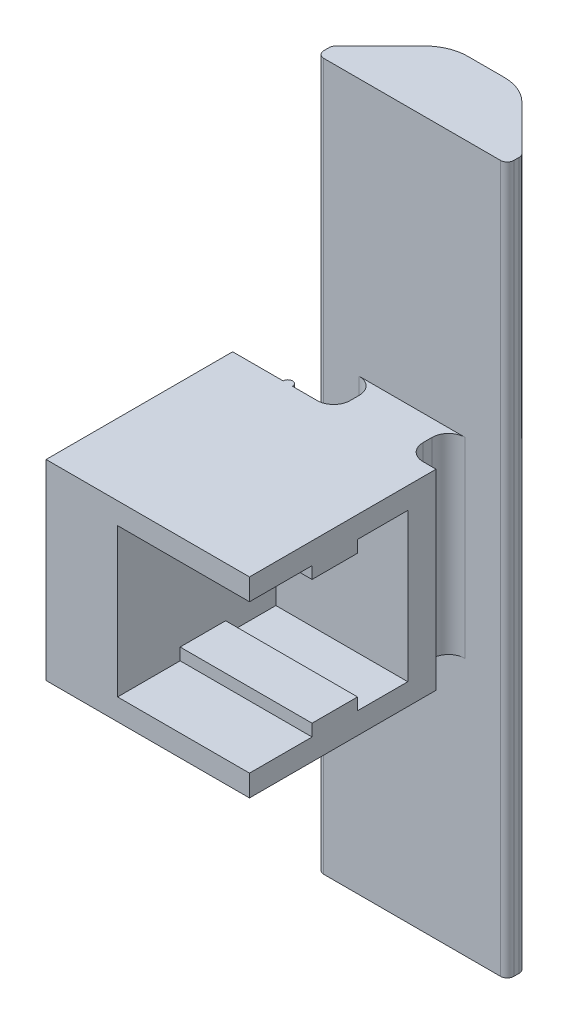
SolidWorks part; units mm, degrees
ref_plane "Front Plane" through (0, 0, 0) normal (0, 0, 1) x (1, 0, 0)
ref_plane "Top Plane" through (0, 0, 0) normal (0, 1, 0) x (1, 0, 0)
ref_plane "Right Plane" through (0, 0, 0) normal (1, 0, 0) x (0, 0, -1)
sketch "Sketch15" plane through (0, 0, 0) normal (0, 1, 0) x (1, 0, 0)
  line L0 (-3.864, 1.5536) -> (-3.864, 2.5104) construction
  line L1 (-5.6176, 4.264) -> (-9.3853, 4.264)
  line L2 (-10.087, 4.9657) -> (-10.087, 5.534)
  line L3 (-9.8815, 6.0301) -> (-5.1506, 10.761)
  line L4 (-1.9335, 12.0936) -> (1.9335, 12.0936)
  line L5 (5.1506, 10.761) -> (9.8815, 6.0301)
  line L6 (10.087, 5.534) -> (10.087, 4.9657)
  line L7 (9.3853, 4.264) -> (5.6176, 4.264)
  line L8 (3.864, 2.5104) -> (3.864, 1.5536) construction
  line L9 (-5.6176, 4.264) -> (5.6176, 4.264)
  line L130 (-14.3277, 0) -> (-9.4961, 0) construction
  line L131 (-7.9763, 0) -> (-5.6176, 0) construction
  line L132 (-4.064, 1.5536) -> (-4.064, 2.5104) construction
  line L133 (-5.6176, 4.064) -> (-9.3853, 4.064) construction
  line L134 (-10.287, 4.9657) -> (-10.287, 5.534) construction
  line L135 (-10.0229, 6.1716) -> (-5.2921, 10.9024) construction
  line L136 (-1.9335, 12.2936) -> (1.9335, 12.2936) construction
  line L137 (5.2921, 10.9024) -> (10.0229, 6.1716) construction
  line L138 (10.287, 5.534) -> (10.287, 4.9657) construction
  line L139 (9.3853, 4.064) -> (5.6176, 4.064) construction
  line L140 (4.064, 2.5104) -> (4.064, 1.5536) construction
  line L141 (5.6176, 0) -> (7.9763, 0) construction
  line L142 (9.4961, 0) -> (14.3277, 0) construction
  arc A0 (-5.6176, -0.2) -> (-3.864, 1.5536) centre (-5.6176, 1.5536) ccw construction
  arc A1 (-3.864, 2.5104) -> (-5.6176, 4.264) centre (-5.6176, 2.5104) ccw construction
  arc A2 (-10.087, 4.9657) -> (-9.3853, 4.264) centre (-9.3853, 4.9657) ccw
  arc A3 (-9.8815, 6.0301) -> (-10.087, 5.534) centre (-9.3853, 5.534) ccw
  arc A4 (-1.9335, 12.0936) -> (-5.1506, 10.761) centre (-1.9335, 7.5438) ccw
  arc A5 (5.1506, 10.761) -> (1.9335, 12.0936) centre (1.9335, 7.5438) ccw
  arc A6 (10.087, 5.534) -> (9.8815, 6.0301) centre (9.3853, 5.534) ccw
  arc A7 (9.3853, 4.264) -> (10.087, 4.9657) centre (9.3853, 4.9657) ccw
  arc A8 (5.6176, 4.264) -> (3.864, 2.5104) centre (5.6176, 2.5104) ccw construction
  arc A9 (3.864, 1.5536) -> (5.6176, -0.2) centre (5.6176, 1.5536) ccw construction
  arc A151 (-19.05, 3.2025) -> (-15.8475, 0) centre (-15.8751, 3.1749) ccw construction
  arc A152 (-14.3277, 0) -> (-15.8475, 0) centre (-15.0876, 0.0567) ccw construction
  arc A153 (-7.9763, 0) -> (-9.4961, 0) centre (-8.7362, 0.0567) ccw construction
  arc A154 (-5.6176, 0) -> (-4.064, 1.5536) centre (-5.6176, 1.5536) ccw construction
  arc A155 (-4.064, 2.5104) -> (-5.6176, 4.064) centre (-5.6176, 2.5104) ccw construction
  arc A156 (-10.287, 4.9657) -> (-9.3853, 4.064) centre (-9.3853, 4.9657) ccw construction
  arc A157 (-10.0229, 6.1716) -> (-10.287, 5.534) centre (-9.3853, 5.534) ccw construction
  arc A158 (-1.9335, 12.2936) -> (-5.2921, 10.9024) centre (-1.9335, 7.5438) ccw construction
  arc A159 (5.2921, 10.9024) -> (1.9335, 12.2936) centre (1.9335, 7.5438) ccw construction
  arc A160 (10.287, 5.534) -> (10.0229, 6.1716) centre (9.3853, 5.534) ccw construction
  arc A161 (9.3853, 4.064) -> (10.287, 4.9657) centre (9.3853, 4.9657) ccw construction
  arc A162 (5.6176, 4.064) -> (4.064, 2.5104) centre (5.6176, 2.5104) ccw construction
  arc A163 (4.064, 1.5536) -> (5.6176, 0) centre (5.6176, 1.5536) ccw construction
  arc A164 (9.4961, 0) -> (7.9763, 0) centre (8.7362, 0.0567) ccw construction
  point P0 (11.9119, 0)
  dimension "D1" = 0.2
extrude "Boss-Extrude6" add sketch "Sketch15" along normal mid plane 75
sketch "Sketch1" plane through (0, 0, 0) normal (0, 1, 0) x (1, 0, 0)
  line L0 (-14.5877, -0.2) -> (-14.5877, -20)
  line L5 (7, -0.2) -> (7, -20)
  line L6 (5.6176, -0.2) -> (8.2363, -0.2) construction
  line L7 (-14.5877, -20) -> (7, -20)
  line L14 (-14.3277, 0) -> (-9.4961, 0) construction
  line L16 (5.6176, 0) -> (7.9763, 0) construction
  line L17 (4.064, 2.5104) -> (4.064, 1.5536) construction
  line L18 (9.3853, 4.064) -> (5.6176, 4.064) construction
  line L19 (-7.9763, 0) -> (-5.6176, 0) construction
  line L20 (-4.064, 1.5536) -> (-4.064, 2.5104) construction
  line L21 (-5.6176, 4.064) -> (-9.3853, 4.064) construction
  line L22 (-14.5877, -0.2) -> (-9.2361, -0.2)
  line L23 (-8.2363, -0.2) -> (-5.6176, -0.2)
  line L24 (-3.864, 1.5536) -> (-3.864, 2.5104)
  line L25 (5.6176, 4.264) -> (5.6176, 5)
  line L27 (3.864, 2.5104) -> (3.864, 1.5536)
  line L28 (5.6176, -0.2) -> (7, -0.2)
  line L30 (9.3853, 4.264) -> (5.6176, 4.264) construction
  line L31 (-5.6176, 4.264) -> (-9.3853, 4.264) construction
  line L32 (5.6176, 5) -> (-5.6176, 5)
  line L33 (-5.6176, 5) -> (-5.6176, 4.264)
  line L35 (9.2361, -0.2) -> (14.5877, -0.2) construction
  line L36 (9.4961, 0) -> (14.3277, 0) construction
  arc A0 (-8.2363, -0.2) -> (-9.2361, -0.2) centre (-8.7362, -0.2) ccw
  arc A10 (-19.05, 3.2025) -> (-15.8475, 0) centre (-15.8751, 3.1749) ccw construction
  arc A11 (-14.3277, 0) -> (-15.8475, 0) centre (-15.0876, 0.0567) ccw construction
  arc A12 (-7.9763, 0) -> (-9.4961, 0) centre (-8.7362, 0.0567) ccw construction
  arc A15 (9.4961, 0) -> (7.9763, 0) centre (8.7362, 0.0567) ccw construction
  arc A16 (4.064, 1.5536) -> (5.6176, 0) centre (5.6176, 1.5536) ccw construction
  arc A17 (5.6176, 4.064) -> (4.064, 2.5104) centre (5.6176, 2.5104) ccw construction
  arc A18 (-5.6176, 0) -> (-4.064, 1.5536) centre (-5.6176, 1.5536) ccw construction
  arc A19 (-4.064, 2.5104) -> (-5.6176, 4.064) centre (-5.6176, 2.5104) ccw construction
  arc A23 (-5.6176, -0.2) -> (-3.864, 1.5536) centre (-5.6176, 1.5536) ccw
  arc A24 (-3.864, 2.5104) -> (-5.6176, 4.264) centre (-5.6176, 2.5104) ccw
  arc A25 (5.6176, 4.264) -> (3.864, 2.5104) centre (5.6176, 2.5104) ccw
  arc A26 (3.864, 1.5536) -> (5.6176, -0.2) centre (5.6176, 1.5536) ccw
  arc A30 (15.5934, -0.1883) -> (14.5877, -0.2) centre (15.0876, 0.0567) ccw construction
  arc A31 (15.5934, -0.1883) -> (19.25, 3.2043) centre (15.8751, 3.1749) ccw construction
  arc A32 (15.8475, 0) -> (19.05, 3.2025) centre (15.8751, 3.1749) ccw construction
  arc A33 (15.8475, 0) -> (14.3277, 0) centre (15.0876, 0.0567) ccw construction
  arc A34 (-19.25, 3.2043) -> (-15.5934, -0.1883) centre (-15.8751, 3.1749) ccw construction
  arc A35 (-14.5877, -0.2) -> (-15.5934, -0.1883) centre (-15.0876, 0.0567) ccw construction
  arc A36 (-8.2363, -0.2) -> (-9.2361, -0.2) centre (-8.7362, 0.0567) ccw construction
  arc A37 (9.2361, -0.2) -> (8.2363, -0.2) centre (8.7362, 0.0567) ccw construction
  point P0 (0, 0)
  point P67 (0, 0)
  dimension "D1" = 5
  dimension "D2" = 20
  dimension "D4" = 7
  dimension "D3" = 0.2
extrude "Boss-Extrude1" add sketch "Sketch1" along normal mid plane 20.32
sketch "Sketch12" plane through (7, 0, 0) normal (1, 0, 0) x (0, 0, -1)
  line L0 (-22.36, 7.874) -> (-22.36, -7.874)
  line L2 (-22.36, 7.874) -> (-13.36, 7.874)
  line L3 (-13.36, 7.874) -> (-13.36, 6.604)
  line L4 (-13.36, 6.604) -> (-8.534, 6.604)
  line L5 (-8.534, 6.604) -> (-8.534, 7.874)
  line L6 (-8.534, 7.874) -> (-3.2, 7.874)
  line L7 (-3.2, 7.874) -> (-3.2, -7.874)
  line L8 (-3.2, -7.874) -> (-8.534, -7.874)
  line L9 (-8.534, -7.874) -> (-8.534, -6.604)
  line L10 (-8.534, -6.604) -> (-13.36, -6.604)
  line L11 (-13.36, -6.604) -> (-13.36, -7.874)
  line L12 (-13.36, -7.874) -> (-22.36, -7.874)
  line L13 (-0.2, 0) -> (-22.36, 0) construction
  line L14 (-0.2, 10.16) -> (-0.2, -10.16) construction
  point P5 (-22.36, 0)
  point P14 (-0.2, 0)
  dimension "D1" = 15.748
  dimension "D2" = 9
  dimension "D3" = 4.826
  dimension "D4" = 5.334
  dimension "D5" = 1.27
  dimension "D6" = 3.2
extrude "Cut-Extrude4" cut sketch "Sketch12" against normal blind 14
